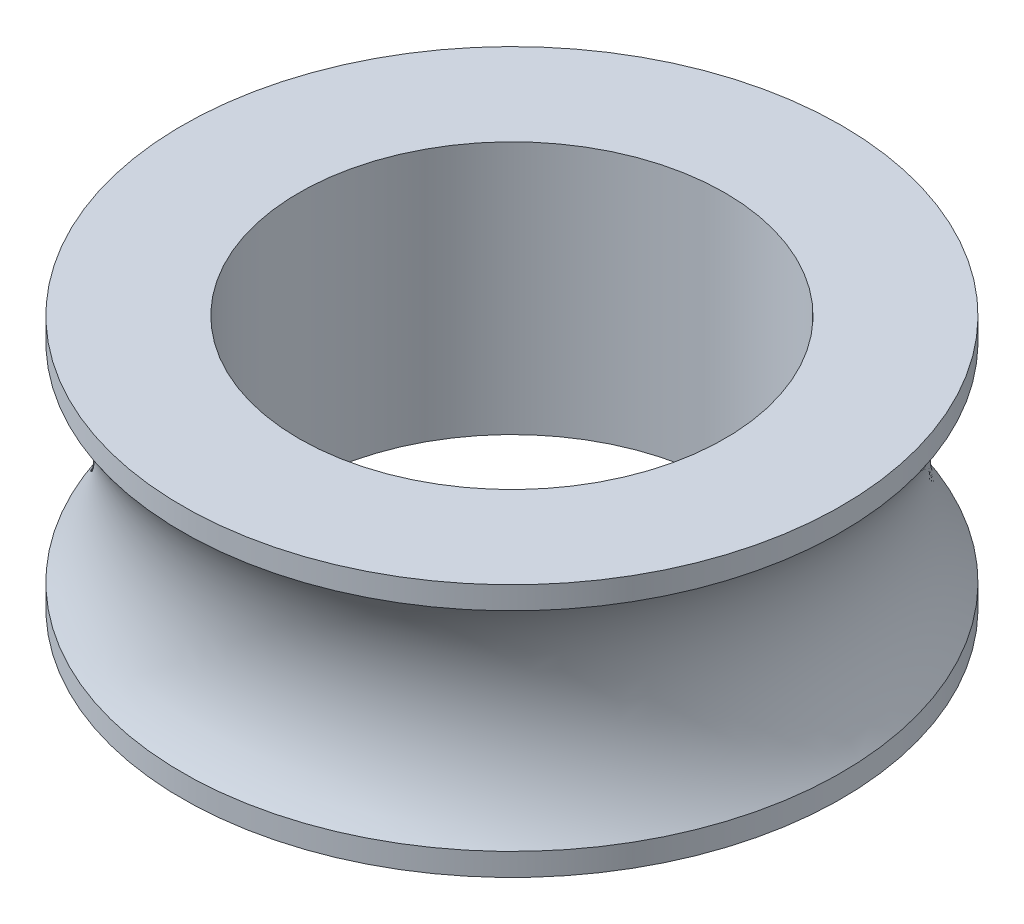
SolidWorks part; units mm, degrees
material "聚脂树脂"
ref_plane "前视基准面" through (0, 0, 0) normal (0, 0, 1) x (1, 0, 0)
ref_plane "上视基准面" through (0, 0, 0) normal (0, 1, 0) x (1, 0, 0)
ref_plane "右视基准面" through (0, 0, 0) normal (1, 0, 0) x (0, 0, -1)
sketch "草图1" plane through (0, 0, 0) normal (0, 0, 1) x (1, 0, 0)
  line L0 (39, 27.3288) -> (39, 30)
  line L1 (0, 0) -> (39, 0)
  line L2 (0, 0) -> (0, 30)
  line L3 (0, 30) -> (39, 30)
  line L4 (39, 0) -> (39, 2.6712)
  arc A0 (39, 2.6712) -> (39, 27.3288) centre (56, 15) cw
  point P15 (35, 15)
  dimension "D3" = 21
  dimension "D1" = 30
  dimension "D2" = 39
  dimension "D4" = 35
revolve "旋转1" add sketch "草图1" angle 360 about L2
sketch "草图2" plane through (0, 30, 0) normal (0, 1, 0) x (1, 0, 0)
  circle A0 centre (0, 0) radius 25.2
  dimension "D1" = 50.4
extrude "切除-拉伸1" cut sketch "草图2" against normal through all
ref_plane "基准面1" through (0, 15, 0) normal (0, -1, 0) x (-1, 0, 0)
